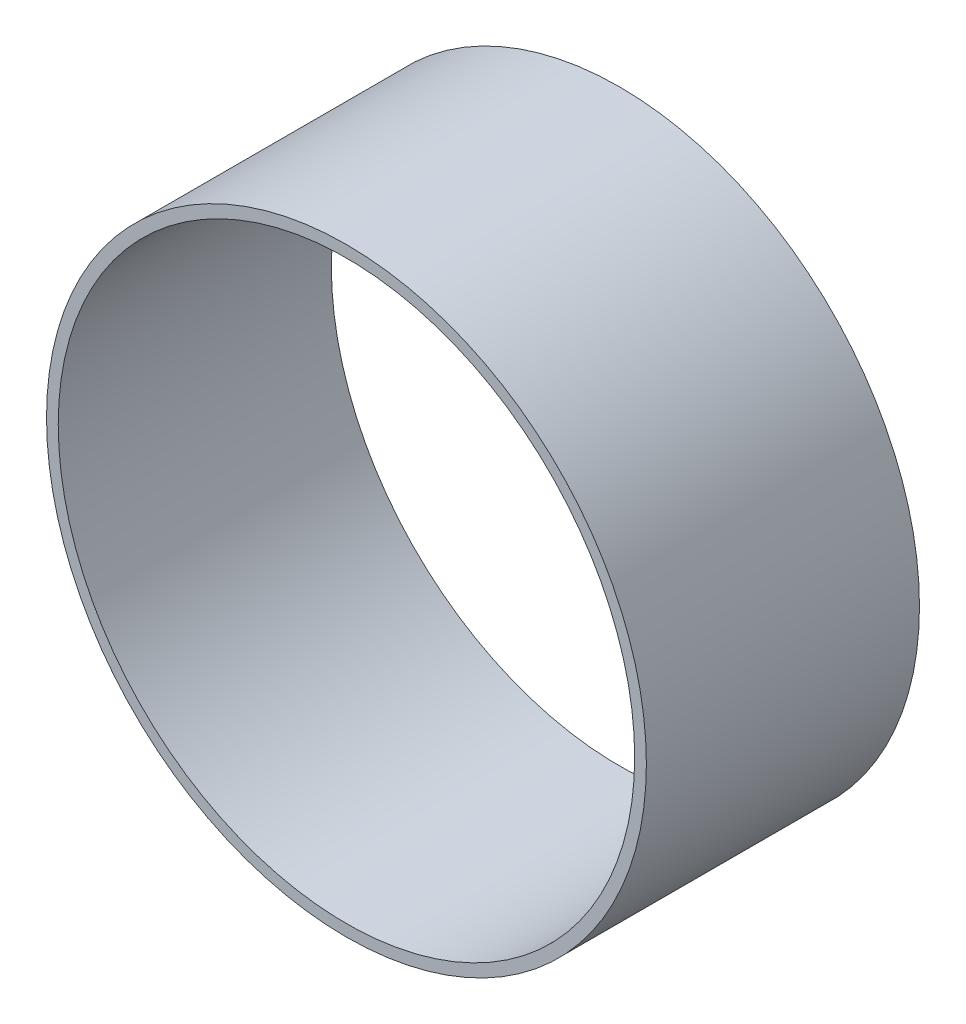
SolidWorks part; units mm, degrees
ref_plane "Спереди" through (0, 0, 0) normal (0, 0, 1) x (1, 0, 0)
ref_plane "Сверху" through (0, 0, 0) normal (0, 1, 0) x (1, 0, 0)
ref_plane "Справа" through (0, 0, 0) normal (1, 0, 0) x (0, 0, -1)
sketch "Эскиз1" plane through (0, 0, 0) normal (0, 0, 1) x (1, 0, 0)
  circle A0 centre (0, 0) radius 76.8769
  circle A1 centre (0, 0) radius 73.8769
extrude "Rotor_shell" add sketch "Эскиз1" along normal blind 70 from offset 35
